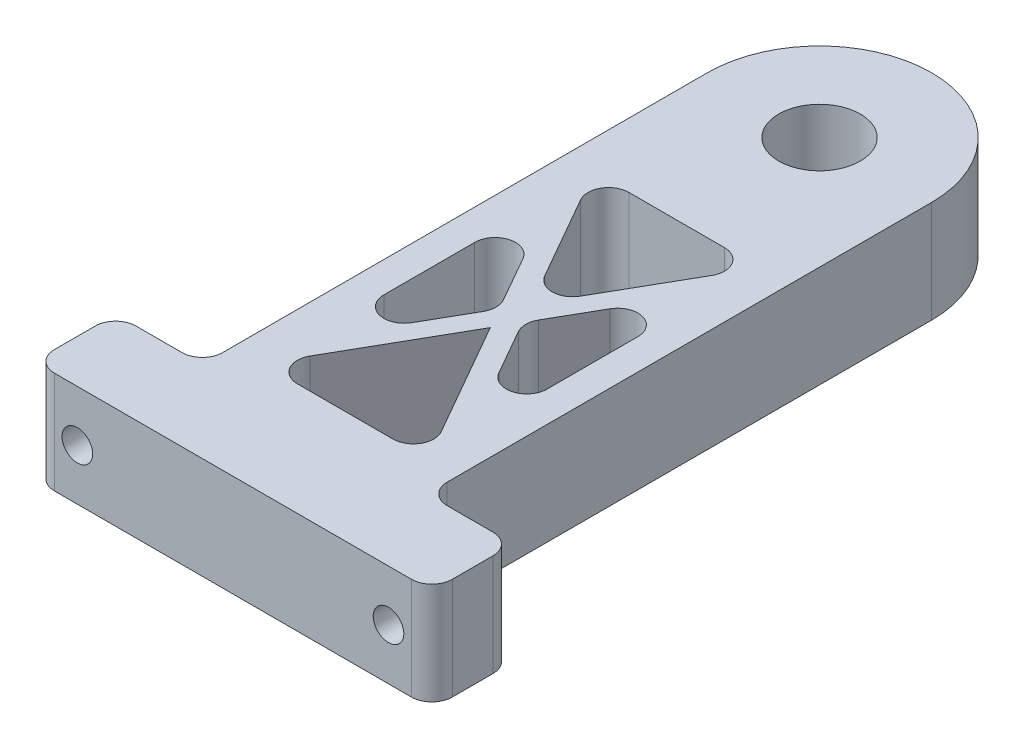
SolidWorks part; units mm, degrees
ref_plane "Front Plane" through (0, 0, 0) normal (0, 0, 1) x (1, 0, 0)
ref_plane "Top Plane" through (0, 0, 0) normal (0, 1, 0) x (1, 0, 0)
ref_plane "Right Plane" through (0, 0, 0) normal (1, 0, 0) x (0, 0, -1)
sketch "Sketch1" plane through (0, 0, 0) normal (0, 1, 0) x (1, 0, 0)
  line L0 (-11, 0) -> (-11, -49.5)
  line L1 (-11, -49.5) -> (-19.5, -49.5)
  line L2 (-19.5, -49.5) -> (-19.5, -57.5)
  line L3 (-19.5, -57.5) -> (19.5, -57.5)
  line L4 (19.5, -57.5) -> (19.5, -49.5)
  line L5 (19.5, -49.5) -> (11, -49.5)
  line L6 (11, -49.5) -> (11, 0)
  line L7 (-11, -11) -> (11, -11)
  line L8 (-11, -11) -> (0, -30.25)
  line L9 (-11, -49.5) -> (11, -49.5)
  line L10 (0, -30.25) -> (11, -11)
  line L11 (0, -30.25) -> (-11, -49.5)
  line L12 (11, -49.5) -> (0, -30.25)
  line L13 (-11, -49.5) -> (11, -49.5)
  line L14 (-10.1318, -10.5039) -> (0.8682, -29.7539)
  line L15 (0.8682, -30.7461) -> (-10.1318, -49.9961)
  line L16 (-0.8682, -29.7539) -> (10.1318, -10.5039)
  line L17 (10.1318, -49.9961) -> (-0.8682, -30.7461)
  line L18 (-11.8682, -11.4961) -> (-1.1518, -30.25)
  line L19 (-1.1518, -30.25) -> (-11.8682, -49.0039)
  line L20 (11.8682, -49.0039) -> (1.1518, -30.25)
  line L21 (1.1518, -30.25) -> (11.8682, -11.4961)
  line L22 (-8, -18.2656) -> (-8, -42.2344)
  line L23 (-8.134, -46.5) -> (8.134, -46.5)
  line L24 (8, -18.2656) -> (8, -42.2344)
  line L25 (-8.134, -14) -> (8.134, -14)
  line L26 (-8, -42.2344) -> (-8.134, -46.5)
  line L27 (8.134, -46.5) -> (8, -42.2344)
  line L28 (-8, -18.2656) -> (-8.134, -14)
  line L29 (8, -18.2656) -> (8.134, -14)
  circle A0 centre (0, 0) radius 11
  circle A1 centre (0, 0) radius 57.5 construction
  circle A2 centre (0, 0) radius 4
  dimension "D3" = 22
  dimension "D5" = 115
  dimension "D1" = 8
  dimension "D2" = 8.5
  dimension "D4" = 8
  dimension "D6" = 19.25
  dimension "D10" = 3
  dimension "D11" = 3
  dimension "D12" = 3
  dimension "D13" = 3
  dimension "D7" = 1
  dimension "D8" = 1
  dimension "D9" = 1
extrude "Boss-Extrude1" add sketch "Sketch1" along normal blind 10
fillet "Fillet1" radius 2 17 edges at (11, 5, 49.5) (19.5, 5, 49.5) (19.5, 5, 57.5) (-19.5, 5, 57.5) (-19.5, 5, 49.5) (-11, 5, 49.5) (-1.1518, 5, 30.25) (1.1518, 5, 30.25) (8, 5, 18.2656) (8.134, 5, 14) (-8.134, 5, 14) (-8, 5, 18.2656) (8.134, 5, 46.5) (-8.134, 5, 46.5) (-8, 5, 42.2344) (8, 5, 42.2344) (0, 5, 28.2344)
sketch "Sketch2" plane through (0, 0, 49.5) normal (0, 0, -1) x (-1, 0, 0)
  line L0 (-13, 0) -> (-17.5, 10) construction
  line L1 (13, 0) -> (17.5, 10) construction
  line L4 (-17.5, 0) -> (-13, 0)
  line L5 (-13, 0) -> (-13, 10)
  line L6 (-13, 10) -> (-17.5, 10)
  line L7 (-17.5, 10) -> (-17.5, 0)
  line L8 (-17.5, 0) -> (-13, 0)
  line L10 (-13, 10) -> (-17.5, 10)
  line L11 (-17.5, 10) -> (-17.5, 0)
  line L12 (13, 0) -> (17.5, 0)
  line L13 (17.5, 0) -> (17.5, 10)
  line L14 (17.5, 10) -> (13, 10)
  line L15 (13, 10) -> (13, 0)
  line L16 (13, 0) -> (17.5, 0)
  line L17 (17.5, 0) -> (17.5, 10)
  line L18 (17.5, 10) -> (13, 10)
  line L24 (-13, 0) -> (-13, 10)
  line L25 (13, 10) -> (13, 0)
  circle A0 centre (-15.25, 5) radius 1.5
  circle A1 centre (15.25, 5) radius 1.5
  dimension "D3" = 3
  dimension "D1" = 0
  dimension "D2" = 0
extrude "Cut-Extrude1" cut sketch "Sketch2" against normal through all contours A0 | A1
